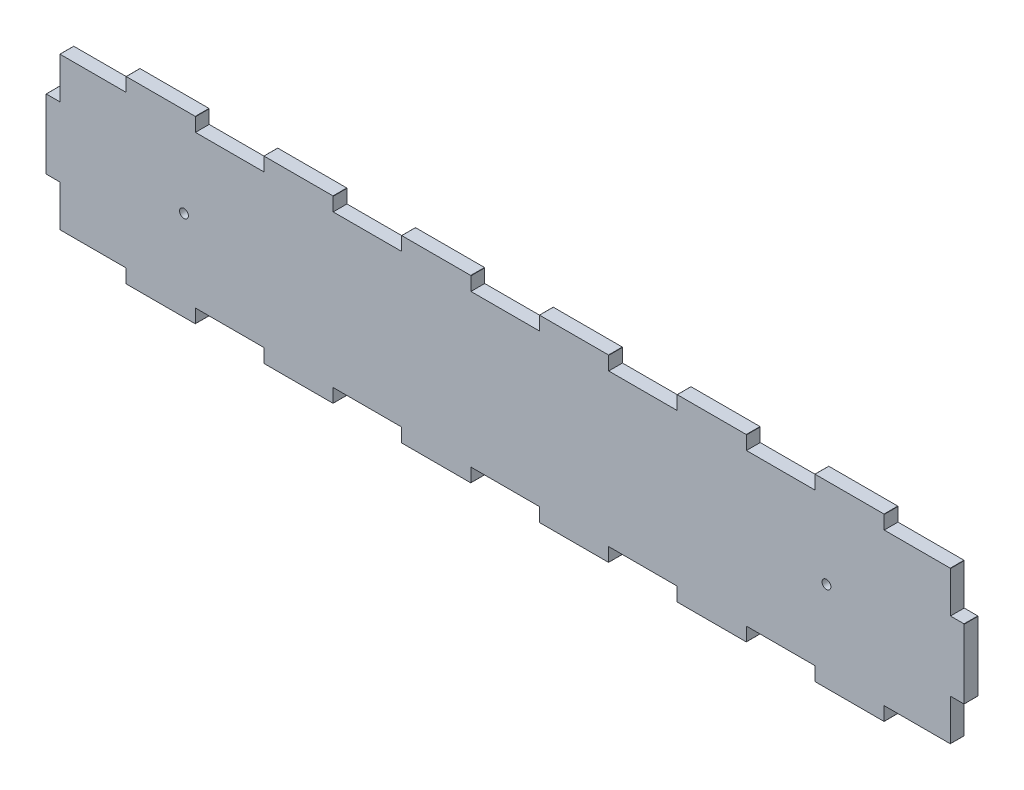
SolidWorks part; units mm, degrees
ref_plane "Front Plane" through (0, 0, 0) normal (0, 0, 1) x (1, 0, 0)
ref_plane "Top Plane" through (0, 0, 0) normal (0, 1, 0) x (1, 0, 0)
ref_plane "Right Plane" through (0, 0, 0) normal (1, 0, 0) x (0, 0, -1)
sketch "Model" plane through (0, 0, 0) normal (0, 0, 1) x (1, 0, 0)
  line L0 (-112.44, -32.58) -> (-112.43, -32.57)
  line L1 (-112.43, -32.57) -> (-112.42, -32.55)
  line L2 (-112.42, -32.55) -> (-112.41, -32.54)
  line L3 (-112.41, -32.54) -> (-112.4, -32.52)
  line L4 (-112.4, -32.52) -> (-112.4, -27.6)
  line L5 (-112.4, -27.6) -> (-87.6, -27.6)
  line L6 (-87.6, -27.6) -> (-87.6, -32.52)
  line L7 (-87.6, -32.52) -> (-87.58, -32.56)
  line L8 (-87.58, -32.56) -> (-87.57, -32.57)
  line L9 (-87.57, -32.57) -> (-87.55, -32.58)
  line L10 (-87.55, -32.58) -> (-87.54, -32.59)
  line L11 (-87.54, -32.59) -> (-87.52, -32.6)
  line L12 (-87.52, -32.6) -> (-62.48, -32.6)
  line L13 (-62.48, -32.6) -> (-62.44, -32.58)
  line L14 (-62.44, -32.58) -> (-62.43, -32.57)
  line L15 (-62.43, -32.57) -> (-62.42, -32.55)
  line L16 (-62.42, -32.55) -> (-62.41, -32.54)
  line L17 (-62.41, -32.54) -> (-62.4, -32.52)
  line L18 (-62.4, -32.52) -> (-62.4, -27.6)
  line L19 (-62.4, -27.6) -> (-37.6, -27.6)
  line L20 (-37.6, -27.6) -> (-37.6, -32.52)
  line L21 (-37.6, -32.52) -> (-37.58, -32.56)
  line L22 (-37.58, -32.56) -> (-37.57, -32.57)
  line L23 (-37.57, -32.57) -> (-37.55, -32.58)
  line L24 (-37.55, -32.58) -> (-37.54, -32.59)
  line L25 (-37.54, -32.59) -> (-37.52, -32.6)
  line L26 (-37.52, -32.6) -> (-12.48, -32.6)
  line L27 (-12.48, -32.6) -> (-12.44, -32.58)
  line L28 (-12.44, -32.58) -> (-12.43, -32.57)
  line L29 (-12.43, -32.57) -> (-12.42, -32.55)
  line L30 (-12.42, -32.55) -> (-12.41, -32.54)
  line L31 (-12.41, -32.54) -> (-12.4, -32.52)
  line L32 (-12.4, -32.52) -> (-12.4, -27.6)
  line L33 (-12.4, -27.6) -> (12.4, -27.6)
  line L34 (12.4, -27.6) -> (12.4, -32.52)
  line L35 (12.4, -32.52) -> (12.42, -32.56)
  line L36 (12.42, -32.56) -> (12.43, -32.57)
  line L37 (12.43, -32.57) -> (12.45, -32.58)
  line L38 (12.45, -32.58) -> (12.46, -32.59)
  line L39 (12.46, -32.59) -> (12.48, -32.6)
  line L40 (12.48, -32.6) -> (37.52, -32.6)
  line L41 (37.52, -32.6) -> (37.56, -32.58)
  line L42 (37.56, -32.58) -> (37.57, -32.57)
  line L43 (37.57, -32.57) -> (37.58, -32.55)
  line L44 (37.58, -32.55) -> (37.59, -32.54)
  line L45 (37.59, -32.54) -> (37.6, -32.52)
  line L46 (37.6, -32.52) -> (37.6, -27.6)
  line L47 (37.6, -27.6) -> (62.4, -27.6)
  line L48 (62.4, -27.6) -> (62.4, -32.52)
  line L49 (62.4, -32.52) -> (62.42, -32.56)
  line L50 (62.42, -32.56) -> (62.43, -32.57)
  line L51 (62.43, -32.57) -> (62.45, -32.58)
  line L52 (62.45, -32.58) -> (62.46, -32.59)
  line L53 (62.46, -32.59) -> (62.48, -32.6)
  line L54 (62.48, -32.6) -> (87.52, -32.6)
  line L55 (87.52, -32.6) -> (87.56, -32.58)
  line L56 (87.56, -32.58) -> (87.57, -32.57)
  line L57 (87.57, -32.57) -> (87.58, -32.55)
  line L58 (87.58, -32.55) -> (87.59, -32.54)
  line L59 (87.59, -32.54) -> (87.6, -32.52)
  line L60 (87.6, -32.52) -> (87.6, -27.6)
  line L61 (87.6, -27.6) -> (112.4, -27.6)
  line L62 (112.4, -27.6) -> (112.4, -32.52)
  line L63 (112.4, -32.52) -> (112.42, -32.56)
  line L64 (112.42, -32.56) -> (112.43, -32.57)
  line L65 (112.43, -32.57) -> (112.45, -32.58)
  line L66 (112.45, -32.58) -> (112.46, -32.59)
  line L67 (112.46, -32.59) -> (112.48, -32.6)
  line L68 (112.48, -32.6) -> (137.52, -32.6)
  line L69 (137.52, -32.6) -> (137.56, -32.58)
  line L70 (137.56, -32.58) -> (137.57, -32.57)
  line L71 (137.57, -32.57) -> (137.58, -32.55)
  line L72 (137.58, -32.55) -> (137.59, -32.54)
  line L73 (137.59, -32.54) -> (137.6, -32.52)
  line L74 (137.6, -32.52) -> (137.6, -27.6)
  line L75 (137.6, -27.6) -> (161.56, -27.6)
  line L76 (161.56, -27.6) -> (161.6, -27.58)
  line L77 (161.6, -27.58) -> (161.61, -27.57)
  line L78 (161.61, -27.57) -> (161.62, -27.55)
  line L79 (161.62, -27.55) -> (161.63, -27.54)
  line L80 (161.63, -27.54) -> (161.64, -27.52)
  line L81 (161.64, -27.52) -> (161.64, -12.6)
  line L82 (161.64, -12.6) -> (166.56, -12.6)
  line L83 (166.56, -12.6) -> (166.6, -12.58)
  line L84 (166.6, -12.58) -> (166.61, -12.57)
  line L85 (166.61, -12.57) -> (166.62, -12.55)
  line L86 (166.62, -12.55) -> (166.63, -12.54)
  line L87 (166.63, -12.54) -> (166.64, -12.52)
  line L88 (166.64, -12.52) -> (166.64, 12.52)
  line L89 (166.64, 12.52) -> (166.62, 12.56)
  line L90 (166.62, 12.56) -> (166.61, 12.57)
  line L91 (166.61, 12.57) -> (166.59, 12.58)
  line L92 (166.59, 12.58) -> (166.58, 12.59)
  line L93 (166.58, 12.59) -> (166.56, 12.6)
  line L94 (166.56, 12.6) -> (161.64, 12.6)
  line L95 (161.64, 12.6) -> (161.64, 27.52)
  line L96 (161.64, 27.52) -> (161.62, 27.56)
  line L97 (161.62, 27.56) -> (161.61, 27.57)
  line L98 (161.61, 27.57) -> (161.59, 27.58)
  line L99 (161.59, 27.58) -> (161.58, 27.59)
  line L100 (161.58, 27.59) -> (161.56, 27.6)
  line L101 (161.56, 27.6) -> (137.6, 27.6)
  line L102 (137.6, 27.6) -> (137.6, 32.52)
  line L103 (137.6, 32.52) -> (137.58, 32.56)
  line L104 (137.58, 32.56) -> (137.57, 32.57)
  line L105 (137.57, 32.57) -> (137.55, 32.58)
  line L106 (137.55, 32.58) -> (137.54, 32.59)
  line L107 (137.54, 32.59) -> (137.52, 32.6)
  line L108 (137.52, 32.6) -> (112.48, 32.6)
  line L109 (112.48, 32.6) -> (112.44, 32.58)
  line L110 (112.44, 32.58) -> (112.43, 32.57)
  line L111 (112.43, 32.57) -> (112.42, 32.55)
  line L112 (112.42, 32.55) -> (112.41, 32.54)
  line L113 (112.41, 32.54) -> (112.4, 32.52)
  line L114 (112.4, 32.52) -> (112.4, 27.6)
  line L115 (112.4, 27.6) -> (87.6, 27.6)
  line L116 (87.6, 27.6) -> (87.6, 32.52)
  line L117 (87.6, 32.52) -> (87.58, 32.56)
  line L118 (87.58, 32.56) -> (87.57, 32.57)
  line L119 (87.57, 32.57) -> (87.55, 32.58)
  line L120 (87.55, 32.58) -> (87.54, 32.59)
  line L121 (87.54, 32.59) -> (87.52, 32.6)
  line L122 (87.52, 32.6) -> (62.48, 32.6)
  line L123 (62.48, 32.6) -> (62.44, 32.58)
  line L124 (62.44, 32.58) -> (62.43, 32.57)
  line L125 (62.43, 32.57) -> (62.42, 32.55)
  line L126 (62.42, 32.55) -> (62.41, 32.54)
  line L127 (62.41, 32.54) -> (62.4, 32.52)
  line L128 (62.4, 32.52) -> (62.4, 27.6)
  line L129 (62.4, 27.6) -> (37.6, 27.6)
  line L130 (37.6, 27.6) -> (37.6, 32.52)
  line L131 (37.6, 32.52) -> (37.58, 32.56)
  line L132 (37.58, 32.56) -> (37.57, 32.57)
  line L133 (37.57, 32.57) -> (37.55, 32.58)
  line L134 (37.55, 32.58) -> (37.54, 32.59)
  line L135 (37.54, 32.59) -> (37.52, 32.6)
  line L136 (37.52, 32.6) -> (12.48, 32.6)
  line L137 (12.48, 32.6) -> (12.44, 32.58)
  line L138 (12.44, 32.58) -> (12.43, 32.57)
  line L139 (12.43, 32.57) -> (12.42, 32.55)
  line L140 (12.42, 32.55) -> (12.41, 32.54)
  line L141 (12.41, 32.54) -> (12.4, 32.52)
  line L142 (12.4, 32.52) -> (12.4, 27.6)
  line L143 (12.4, 27.6) -> (-12.4, 27.6)
  line L144 (-12.4, 27.6) -> (-12.4, 32.52)
  line L145 (-12.4, 32.52) -> (-12.42, 32.56)
  line L146 (-12.42, 32.56) -> (-12.43, 32.57)
  line L147 (-12.43, 32.57) -> (-12.45, 32.58)
  line L148 (-12.45, 32.58) -> (-12.46, 32.59)
  line L149 (-12.46, 32.59) -> (-12.48, 32.6)
  line L150 (-12.48, 32.6) -> (-37.52, 32.6)
  line L151 (-37.52, 32.6) -> (-37.56, 32.58)
  line L152 (-37.56, 32.58) -> (-37.57, 32.57)
  line L153 (-37.57, 32.57) -> (-37.58, 32.55)
  line L154 (-37.58, 32.55) -> (-37.59, 32.54)
  line L155 (-37.59, 32.54) -> (-37.6, 32.52)
  line L156 (-37.6, 32.52) -> (-37.6, 27.6)
  line L157 (-37.6, 27.6) -> (-62.4, 27.6)
  line L158 (-62.4, 27.6) -> (-62.4, 32.52)
  line L159 (-62.4, 32.52) -> (-62.42, 32.56)
  line L160 (-62.42, 32.56) -> (-62.43, 32.57)
  line L161 (-62.43, 32.57) -> (-62.45, 32.58)
  line L162 (-62.45, 32.58) -> (-62.46, 32.59)
  line L163 (-62.46, 32.59) -> (-62.48, 32.6)
  line L164 (-62.48, 32.6) -> (-87.52, 32.6)
  line L165 (-87.52, 32.6) -> (-87.56, 32.58)
  line L166 (-87.56, 32.58) -> (-87.57, 32.57)
  line L167 (-87.57, 32.57) -> (-87.58, 32.55)
  line L168 (-87.58, 32.55) -> (-87.59, 32.54)
  line L169 (-87.59, 32.54) -> (-87.6, 32.52)
  line L170 (-87.6, 32.52) -> (-87.6, 27.6)
  line L171 (-87.6, 27.6) -> (-112.4, 27.6)
  line L172 (-112.4, 27.6) -> (-112.4, 32.52)
  line L173 (-112.4, 32.52) -> (-112.42, 32.56)
  line L174 (-112.42, 32.56) -> (-112.43, 32.57)
  line L175 (-112.43, 32.57) -> (-112.45, 32.58)
  line L176 (-112.45, 32.58) -> (-112.46, 32.59)
  line L177 (-112.46, 32.59) -> (-112.48, 32.6)
  line L178 (-112.48, 32.6) -> (-137.52, 32.6)
  line L179 (-137.52, 32.6) -> (-137.56, 32.58)
  line L180 (-137.56, 32.58) -> (-137.57, 32.57)
  line L181 (-137.57, 32.57) -> (-137.58, 32.55)
  line L182 (-137.58, 32.55) -> (-137.59, 32.54)
  line L183 (-137.59, 32.54) -> (-137.6, 32.52)
  line L184 (-137.6, 32.52) -> (-137.6, 27.6)
  line L185 (-137.6, 27.6) -> (-161.56, 27.6)
  line L186 (-161.56, 27.6) -> (-161.6, 27.58)
  line L187 (-161.6, 27.58) -> (-161.61, 27.57)
  line L188 (-161.61, 27.57) -> (-161.62, 27.55)
  line L189 (-161.62, 27.55) -> (-161.63, 27.54)
  line L190 (-161.63, 27.54) -> (-161.64, 27.52)
  line L191 (-161.64, 27.52) -> (-161.64, 12.6)
  line L192 (-161.64, 12.6) -> (-166.56, 12.6)
  line L193 (-166.56, 12.6) -> (-166.6, 12.58)
  line L194 (-166.6, 12.58) -> (-166.61, 12.57)
  line L195 (-166.61, 12.57) -> (-166.62, 12.55)
  line L196 (-166.62, 12.55) -> (-166.63, 12.54)
  line L197 (-166.63, 12.54) -> (-166.64, 12.52)
  line L198 (-166.64, 12.52) -> (-166.64, -12.52)
  line L199 (-166.64, -12.52) -> (-166.62, -12.56)
  line L200 (-166.62, -12.56) -> (-166.61, -12.57)
  line L201 (-166.61, -12.57) -> (-166.59, -12.58)
  line L202 (-166.59, -12.58) -> (-166.58, -12.59)
  line L203 (-166.58, -12.59) -> (-166.56, -12.6)
  line L204 (-166.56, -12.6) -> (-161.64, -12.6)
  line L205 (-161.64, -12.6) -> (-161.64, -27.52)
  line L206 (-161.64, -27.52) -> (-161.62, -27.56)
  line L207 (-161.62, -27.56) -> (-161.61, -27.57)
  line L208 (-161.61, -27.57) -> (-161.59, -27.58)
  line L209 (-161.59, -27.58) -> (-161.58, -27.59)
  line L210 (-161.58, -27.59) -> (-161.56, -27.6)
  line L211 (-161.56, -27.6) -> (-137.6, -27.6)
  line L212 (-137.6, -27.6) -> (-137.6, -32.52)
  line L213 (-137.6, -32.52) -> (-137.58, -32.56)
  line L214 (-137.58, -32.56) -> (-137.57, -32.57)
  line L215 (-137.57, -32.57) -> (-137.55, -32.58)
  line L216 (-137.55, -32.58) -> (-137.54, -32.59)
  line L217 (-137.54, -32.59) -> (-137.52, -32.6)
  line L218 (-137.52, -32.6) -> (-112.48, -32.6)
  line L219 (-112.48, -32.6) -> (-112.44, -32.58)
extrude "Boss-Extrude1" add sketch "Model" along normal blind 5
sketch "Sketch1" plane through (0, 0, 5) normal (0, 0, 1) x (1, 0, 0)
  line L0 (0.04, 0.04) -> (0.04, -27.52) construction
  line L1 (-161.56, 27.6) -> (161.64, 27.6) construction
  line L2 (-161.56, 27.6) -> (-161.56, -27.52) construction
  line L3 (-161.56, -27.52) -> (161.64, -27.52) construction
  line L4 (161.64, 27.6) -> (161.64, -27.52) construction
  line L5 (-161.56, 27.6) -> (161.64, -27.52) construction
  line L6 (-161.56, -27.52) -> (161.64, 27.6) construction
  circle A0 centre (-116.565, 0.04) radius 1.6
  circle A1 centre (116.645, 0.04) radius 1.6
  point P4 (0.04, 0.04)
  point P13 (0, 0)
  dimension "D1" = 3.2
  dimension "D2" = 233.21
extrude "Cut-Extrude1" cut sketch "Sketch1" against normal through all
